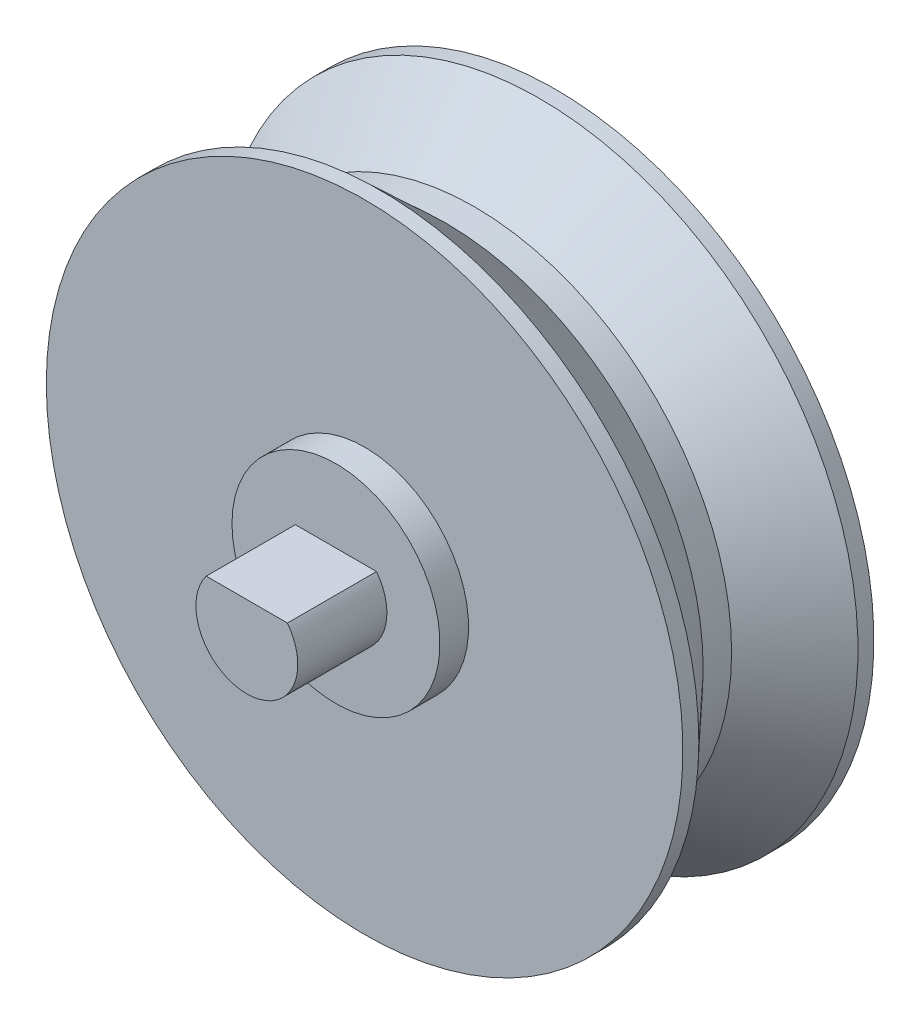
SolidWorks part; units mm, degrees
material "사용자정의 플라스틱"
ref_plane "정면" through (0, 0, 0) normal (0, 0, 1) x (1, 0, 0)
ref_plane "윗면" through (0, 0, 0) normal (0, 1, 0) x (1, 0, 0)
ref_plane "우측면" through (0, 0, 0) normal (1, 0, 0) x (0, 0, -1)
sketch "스케치1" plane through (0, 0, 0) normal (0, 0, 1) x (1, 0, 0)
  line L0 (-3.8249, 2.9) -> (3.8249, 2.9)
  circle A0 centre (0, 0) radius 4.8
  dimension "D1" = 9.6
  dimension "D2" = 2.9
extrude "보스-돌출1" add sketch "스케치1" along normal blind 40 contours L0 A0
ref_plane "평면1" through (0, 0, 8.2) normal (0, 0, -1) x (-1, 0, 0)
sketch "스케치2" plane through (0, 0, 8.2) normal (0, 0, -1) x (-1, 0, 0)
  circle A0 centre (0, 0) radius 9.8
  dimension "D1" = 19.6
extrude "보스-돌출2" add sketch "스케치2" against normal blind 23.4
ref_plane "평면2" through (0, 0, 19.9) normal (0, 0, -1) x (-1, 0, 0)
sketch "스케치3" plane through (0, 0, 19.9) normal (0, 0, -1) x (-1, 0, 0)
  circle A0 centre (0, 0) radius 30
  dimension "D1" = 60
extrude "보스-돌출3" add sketch "스케치3" along normal blind 9 and the other way blind 9
sketch "스케치4" plane through (0, 0, 0) normal (1, 0, 0) x (0, 0, -1)
  line L5 (-19.9, 23) -> (-12.4, 30)
  line L6 (-19.9, -10.78) -> (-19.9, 10.78) construction
  line L7 (-10.9, 30) -> (-28.9, 30) construction
  line L8 (-12.4, 30) -> (-27.4, 30)
  line L9 (-27.4, 30) -> (-19.9, 23)
  line L10 (-28.9, 30) -> (-28.9, -30) construction
  line L11 (4.268, 0) -> (-45.9604, 0) construction
  dimension "D1" = 15
  dimension "D2" = 1.5
  dimension "D3" = 1.5
  dimension "D4" = 7.5
  dimension "D5" = 7
revolve "컷-회전1" cut sketch "스케치4" angle 360 about L11
sketch "스케치5" plane through (0, 0, 19.9) normal (0, 0, -1) x (-1, 0, 0)
  circle A0 centre (0, 0) radius 24.25
  dimension "D1" = 48.5
extrude "보스-돌출4" add sketch "스케치5" along normal blind 2 and the other way blind 2
